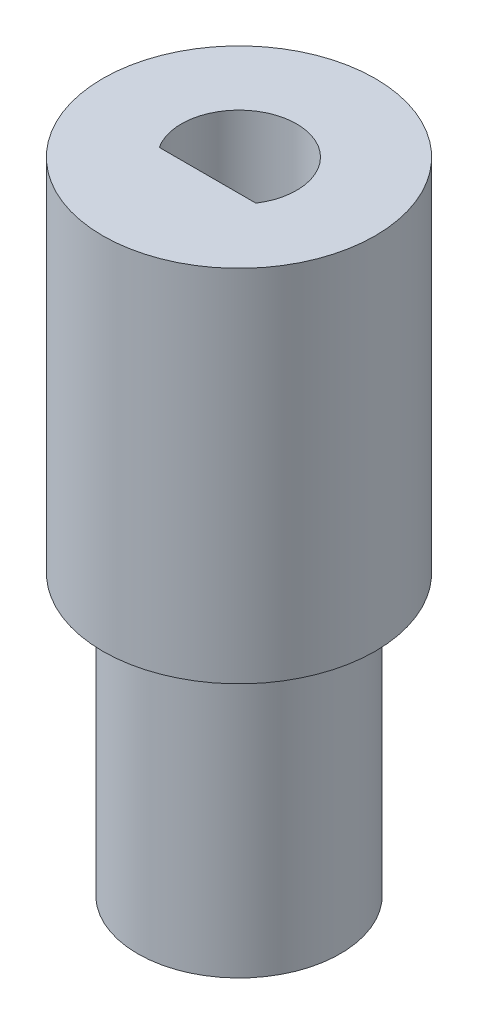
SolidWorks part; units mm, degrees
ref_plane "Ebene vorne" through (0, 0, 0) normal (0, 0, 1) x (1, 0, 0)
ref_plane "Ebene oben" through (0, 0, 0) normal (0, 1, 0) x (1, 0, 0)
ref_plane "Ebene rechts" through (0, 0, 0) normal (1, 0, 0) x (0, 0, -1)
sketch "Skizze1" plane through (0, 0, 0) normal (0, 0, 1) x (1, 0, 0)
  line L0 (0, 0) -> (0, 14.6571) construction
  line L1 (0, 0) -> (-2.9, 0)
  line L2 (-2.9, 0) -> (-2.9, 8)
  line L3 (-2.9, 8) -> (-3.9, 8)
  line L4 (-3.9, 8) -> (-3.9, 18.3)
  line L5 (-3.9, 18.3) -> (0, 18.3)
  line L6 (0, 18.3) -> (0, 0)
  dimension "D1" = 2.9
  dimension "D2" = 3.9
  dimension "D3" = 8
  dimension "D4" = 10.3
revolve "Rotation1" add sketch "Skizze1" angle 360 about L0
sketch "Skizze3" plane through (0, 0, 0) normal (0, -1, 0) x (1, 0, 0)
  line L0 (0, 0) -> (0, 2.4) construction
  line L1 (0, 0) -> (2.4, 0) construction
  line L2 (0.85, 2.2444) -> (0.85, 1.25)
  line L3 (1.25, 0.85) -> (2.2444, 0.85)
  line L4 (2.2444, -0.85) -> (1.25, -0.85)
  line L5 (0.85, -1.25) -> (0.85, -2.2444)
  line L6 (-0.85, -2.2444) -> (-0.85, -1.25)
  line L7 (-1.25, -0.85) -> (-2.2444, -0.85)
  line L8 (-2.2444, 0.85) -> (-1.25, 0.85)
  line L9 (-0.85, 1.25) -> (-0.85, 2.2444)
  arc A0 (2.4, 0) -> (2.2444, 0.85) centre (0, 0) ccw
  arc A1 (0.85, 1.25) -> (1.25, 0.85) centre (1.25, 1.25) ccw
  arc A2 (0.85, 2.2444) -> (0, 2.4) centre (0, 0) ccw
  arc A3 (2.2444, -0.85) -> (2.4, 0) centre (0, 0) ccw
  arc A4 (1.25, -0.85) -> (0.85, -1.25) centre (1.25, -1.25) ccw
  arc A5 (0, -2.4) -> (0.85, -2.2444) centre (0, 0) ccw
  arc A6 (-0.85, -2.2444) -> (0, -2.4) centre (0, 0) ccw
  arc A7 (-0.85, -1.25) -> (-1.25, -0.85) centre (-1.25, -1.25) ccw
  arc A8 (-2.4, 0) -> (-2.2444, -0.85) centre (0, 0) ccw
  arc A9 (-2.2444, 0.85) -> (-2.4, 0) centre (0, 0) ccw
  arc A10 (-1.25, 0.85) -> (-0.85, 1.25) centre (-1.25, 1.25) ccw
  arc A11 (0, 2.4) -> (-0.85, 2.2444) centre (0, 0) ccw
  point P33 (0, 0)
  dimension "D4" = 0.4
  dimension "D1" = 2.4
  dimension "D2" = 0.85
  dimension "D3" = 0.85
  dimension "D5" = 4
extrude "Schnitt-Linear austragen1" cut sketch "Skizze3" against normal blind 8
sketch "Skizze4" plane through (0, 18.3, 0) normal (0, 1, 0) x (1, 0, 0)
  line L0 (-1.3829, -0.9) -> (1.3829, -0.9)
  arc A0 (1.3829, -0.9) -> (-1.3829, -0.9) centre (0, 0) ccw
  point P5 (0, -0.9)
  dimension "D1" = 3.3
  dimension "D2" = 0.9
extrude "Schnitt-Linear austragen2" cut sketch "Skizze4" against normal blind 10
